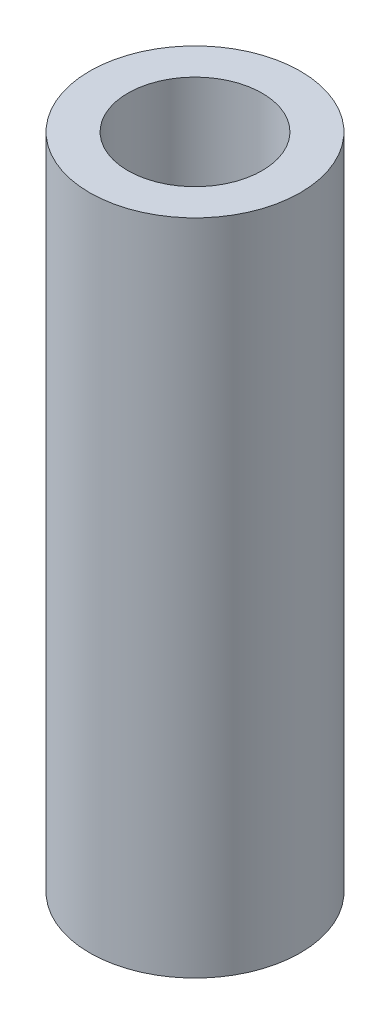
SolidWorks part; units mm, degrees
material "6061-T6 (SS)"
ref_plane "Front Plane" through (0, 0, 0) normal (0, 0, 1) x (1, 0, 0)
ref_plane "Top Plane" through (0, 0, 0) normal (0, 1, 0) x (1, 0, 0)
ref_plane "Right Plane" through (0, 0, 0) normal (1, 0, 0) x (0, 0, -1)
sketch "Sketch1" plane through (0, 0, 0) normal (0, 1, 0) x (1, 0, 0)
  circle A0 centre (0, 0) radius 2.55
  circle A1 centre (0, 0) radius 4
  dimension "D1" = 5.1
  dimension "D2" = 8
extrude "Boss-Extrude1" add sketch "Sketch1" along normal blind 25
